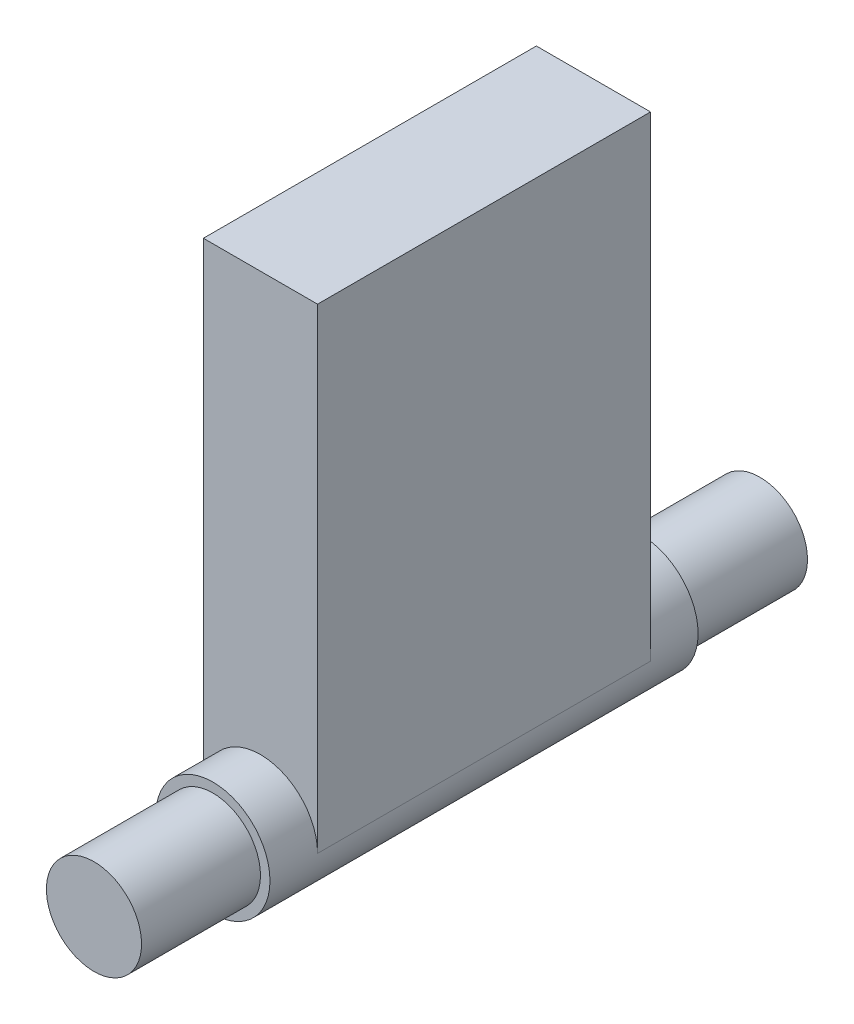
SolidWorks part; units mm, degrees
ref_plane "前视基准面" through (0, 0, 0) normal (0, 0, 1) x (1, 0, 0)
ref_plane "上视基准面" through (0, 0, 0) normal (0, 1, 0) x (1, 0, 0)
ref_plane "右视基准面" through (0, 0, 0) normal (1, 0, 0) x (0, 0, -1)
sketch "草图1" plane through (0, 0, 0) normal (0, 0, 1) x (1, 0, 0)
  circle A0 centre (0, 0) radius 5
  dimension "D1" = 10
extrude "凸台-拉伸1" add sketch "草图1" along normal blind 12.5 contours A0
sketch "草图2" plane through (0, 0, 12.5) normal (0, 0, 1) x (1, 0, 0)
  circle A0 centre (0, 0) radius 6
  dimension "D1" = 12
extrude "凸台-拉伸2" add sketch "草图2" along normal blind 22.5
mirror "镜向2" about plane through (0, 0, 35) normal (0, 0, 1) of "凸台-拉伸2"
sketch "草图3" plane through (0, 0, 57.5) normal (0, 0, 1) x (1, 0, 0)
  circle A0 centre (0, 0) radius 5
  dimension "D1" = 10
extrude "凸台-拉伸3" add sketch "草图3" along normal blind 12.5
sketch "草图4" plane through (0, 0, 0) normal (0, 1, 0) x (1, 0, 0)
  line L0 (-5, -57.5) -> (5, -57.5) construction
  line L1 (6, -12.5) -> (-6, -12.5) construction
  line L2 (6, -57.5) -> (6, -12.5) construction
  line L3 (-6, -12.5) -> (-6, -57.5) construction
  line L4 (-6, -57.5) -> (6, -57.5)
  line L5 (6, -12.5) -> (-6, -12.5)
  line L6 (6, -57.5) -> (6, -12.5)
  line L7 (-6, -12.5) -> (-6, -57.5)
  line L8 (-6, -17.5) -> (6, -17.5)
  line L9 (-6, -52.5) -> (6, -52.5)
  dimension "D1" = 5
  dimension "D2" = 5
extrude "凸台-拉伸4" add sketch "草图4" along normal blind 50 contours L7 L9 L6 L8
